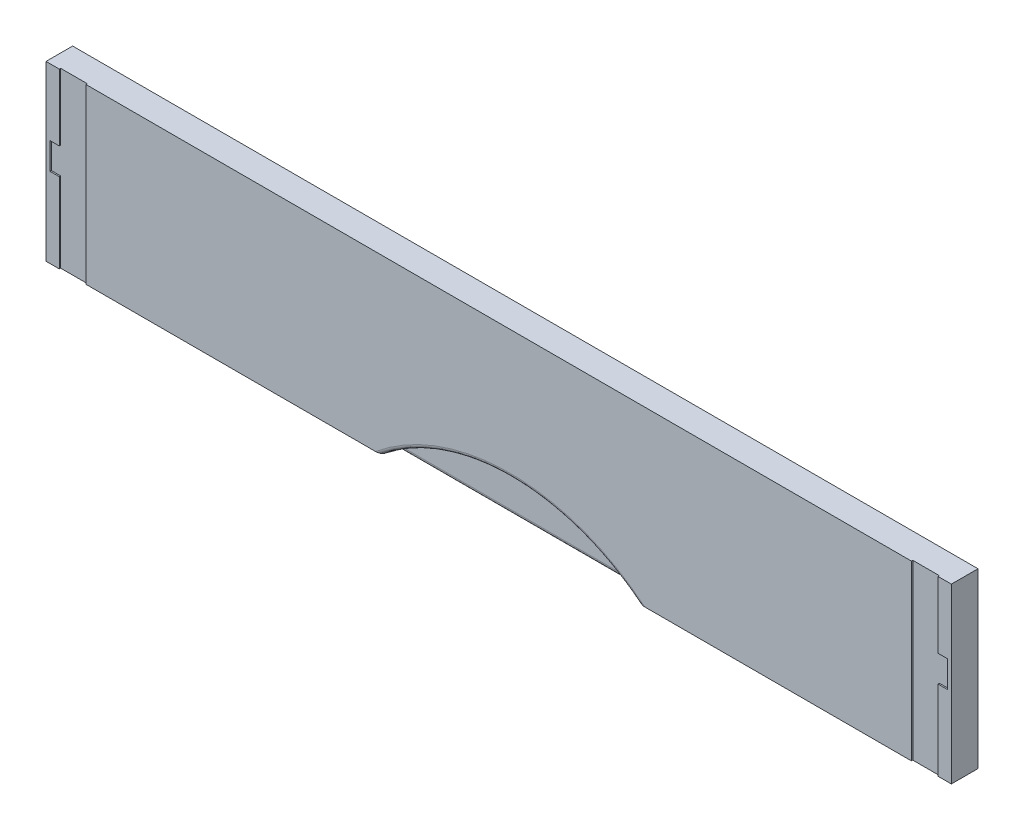
SolidWorks part; units mm, degrees
ref_plane "Alzado" through (0, 0, 0) normal (0, 0, 1) x (1, 0, 0)
ref_plane "Planta" through (0, 0, 0) normal (0, 1, 0) x (1, 0, 0)
ref_plane "Vista lateral" through (0, 0, 0) normal (1, 0, 0) x (0, 0, -1)
sketch "Croquis1" plane through (0, 0, 0) normal (0, 0, 1) x (1, 0, 0)
  line L1 (-340, -65) -> (340, -65)
  line L2 (-340, -65) -> (-340, 65)
  line L3 (-340, 65) -> (340, 65)
  line L4 (340, -65) -> (340, 65)
  line L5 (-340, -65) -> (340, 65) construction
  line L6 (-340, 65) -> (340, -65) construction
  point P0 (0, 0)
  dimension "D1" = 680
  dimension "D2" = 130
extrude "Saliente-Extruir1" add sketch "Croquis1" along normal blind 20
sketch "Croquis4" plane through (0, 0, 20) normal (0, 0, 1) x (1, 0, 0)
  line L0 (-340, -65) -> (340, -65) construction
  line L1 (-87.6885, -65) -> (104.95, -65)
  arc A0 (-87.6885, -65) -> (104.95, -65) centre (8.6308, -187.0322) cw
extrude "Cortar-Extruir6" cut sketch "Croquis4" against normal blind 10
fillet "Redondeo6" radius 3 1 edges at (8.6308, -31.5675, 20)
fillet "Redondeo7" radius 3 1 edges at (8.6308, -65, 10)
sketch "Croquis5" plane through (0, 0, 20) normal (0, 0, 1) x (1, 0, 0)
  line L0 (310, 65) -> (310, -65)
  line L7 (340, 65) -> (-340, 65) construction
  line L17 (0, 0) -> (0, 189.021) construction
  line L26 (109.7208, -65) -> (340, -65) construction
  line L27 (310, -65) -> (330, -65)
  line L28 (330, -65) -> (330, -5)
  line L29 (330, -5) -> (337, -5)
  line L30 (337, -5) -> (337, 15)
  line L31 (337, 15) -> (330, 15)
  line L32 (330, 15) -> (330, 65)
  line L33 (330, 65) -> (310, 65)
  line L34 (340, -65) -> (340, 65) construction
  dimension "D1" = 3
  dimension "D2" = 20
  dimension "D3" = 50
  dimension "D4" = 20
  dimension "D5" = 7
  dimension "D6" = 7
extrude "Cortar-Extruir9" cut sketch "Croquis5" against normal blind 1
sketch "Croquis6" plane through (0, 0, 20) normal (0, 0, 1) x (1, 0, 0)
  line L0 (-310, 65) -> (-310, -65)
  line L1 (310, 65) -> (-340, 65) construction
  line L2 (-340, -65) -> (-92.4593, -65) construction
  line L3 (-310, -65) -> (-330, -65)
  line L4 (-330, -65) -> (-330, -5)
  line L5 (-330, -5) -> (-337, -5)
  line L6 (-337, -5) -> (-337, 15)
  line L7 (-337, 15) -> (-330, 15)
  line L8 (-330, 15) -> (-330, 65)
  line L9 (-330, 65) -> (-310, 65)
  line L10 (-340, 65) -> (-340, -65) construction
  dimension "D1" = 10
  dimension "D2" = 10
  dimension "D3" = 3
  dimension "D4" = 20
  dimension "D5" = 50
  dimension "D6" = 20
extrude "Cortar-Extruir10" cut sketch "Croquis6" against normal blind 1
